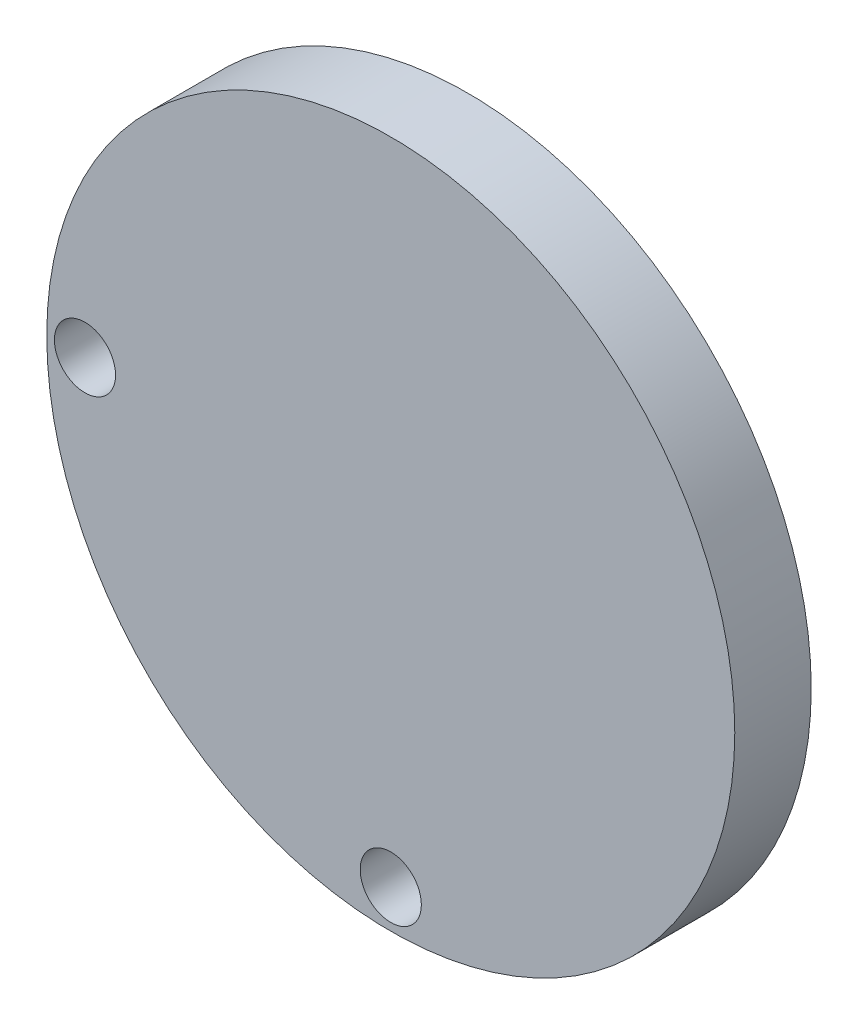
SolidWorks part; units mm, degrees
ref_plane "Front Plane" through (0, 0, 0) normal (0, 0, 1) x (1, 0, 0)
ref_plane "Top Plane" through (0, 0, 0) normal (0, 1, 0) x (1, 0, 0)
ref_plane "Right Plane" through (0, 0, 0) normal (1, 0, 0) x (0, 0, -1)
sketch "Sketch1" plane through (0, 0, 0) normal (0, 0, 1) x (1, 0, 0)
  circle A0 centre (0, 0) radius 45
extrude "Boss-Extrude1" add sketch "Sketch1" along normal mid plane 10
sketch "Sketch2" plane through (0, 0, 5) normal (0, 0, 1) x (1, 0, 0)
  line L0 (0, 0) -> (-40, 0) construction
  line L1 (0, 0) -> (0, -40) construction
  circle A0 centre (-40, 0) radius 4
  circle A1 centre (0, -40) radius 4
extrude "Cut-Extrude1" cut sketch "Sketch2" against normal blind 10
